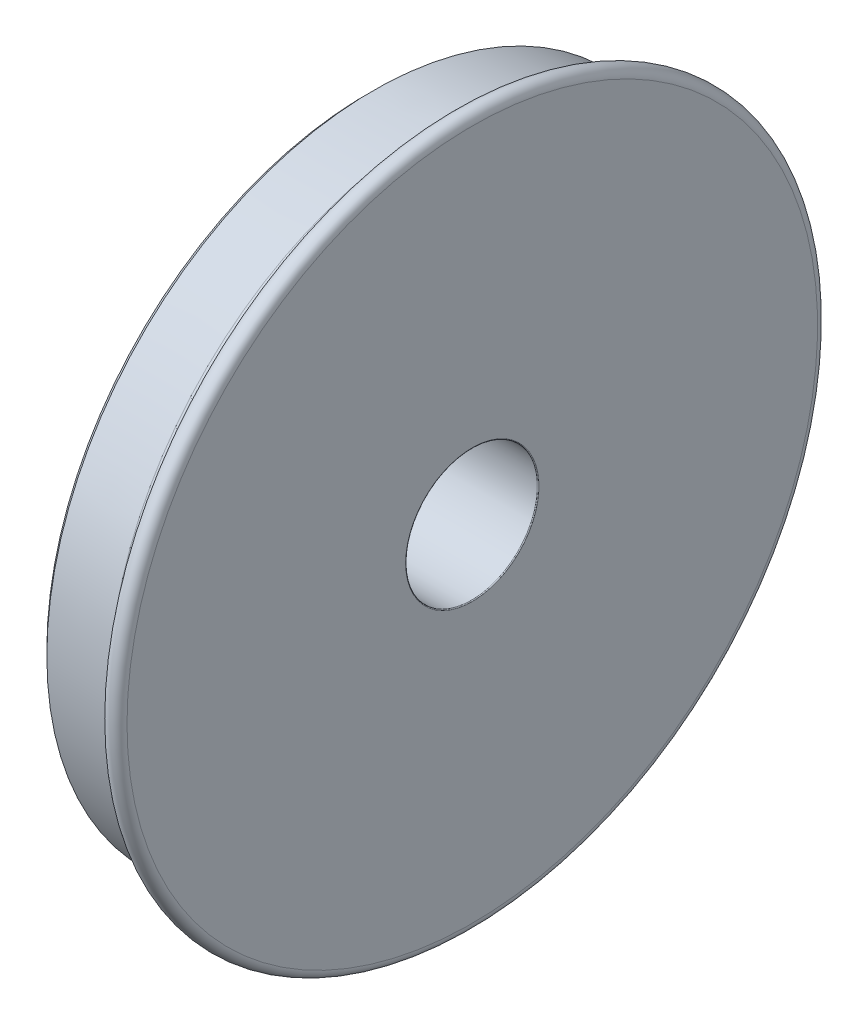
SolidWorks part; units mm, degrees
material "Cast Alloy Steel"
ref_plane "Front Plane" through (0, 0, 0) normal (0, 0, 1) x (1, 0, 0)
ref_plane "Top Plane" through (0, 0, 0) normal (0, 1, 0) x (1, 0, 0)
ref_plane "Right Plane" through (0, 0, 0) normal (1, 0, 0) x (0, 0, -1)
ref_axis "Wheelset axis" through (-146.1647, 0, 0) along (1, 0, 0)
sketch "Sketch1" plane through (0, 0, 0) normal (0, 0, 1) x (1, 0, 0)
  line L0 (0, 20) -> (34.75, 20)
  line L1 (35, 20.25) -> (35, 104.8706)
  line L4 (-146.1647, 0) -> (223.6526, 0) construction
  line L6 (29.4345, 105.3086) -> (29.2384, 104.0709)
  line L9 (3.3, 79.4167) -> (13.3, 79.4167)
  line L10 (13.3, 79.4167) -> (13.3, 31.34)
  line L11 (13.3, 31.34) -> (0, 31.34)
  line L12 (0, 31.34) -> (0, 20)
  line L13 (3.3, 79.4167) -> (3.3, 97.5167)
  line L14 (4.9579, 99.1746) -> (24.4745, 99.8562)
  line L15 (28.5937, 100) -> (3.3, 100) construction
  line L16 (3.3, 97.5167) -> (4.9579, 99.1746)
  arc A0 (34.75, 20) -> (35, 20.25) centre (34.75, 20.25) ccw
  arc A1 (29.2384, 104.0709) -> (24.4745, 99.8562) centre (24.3, 104.8531) cw
  arc A2 (29.4345, 105.3086) -> (35, 104.8706) centre (32.2, 104.8706) cw
  point P19 (3.3, 99.1167)
  dimension "D2" = 0.25
  dimension "D13" = 5
  dimension "D15" = 2.8
  dimension "D1" = 20
  dimension "D3" = 31.7
  dimension "D4" = 3.3
  dimension "D5" = 11.34
  dimension "D6" = 10
  dimension "D7" = 19.7
  dimension "D8" = 9
  dimension "D9" = 2
  dimension "D10" = 1.6
  dimension "D11" = 45
  dimension "D12" = 100
  dimension "D14" = 10.7
revolve "Revolve1" add sketch "Sketch1" angle 360 about axis through (-146.1647, 0, 0) along (1, 0, 0)
